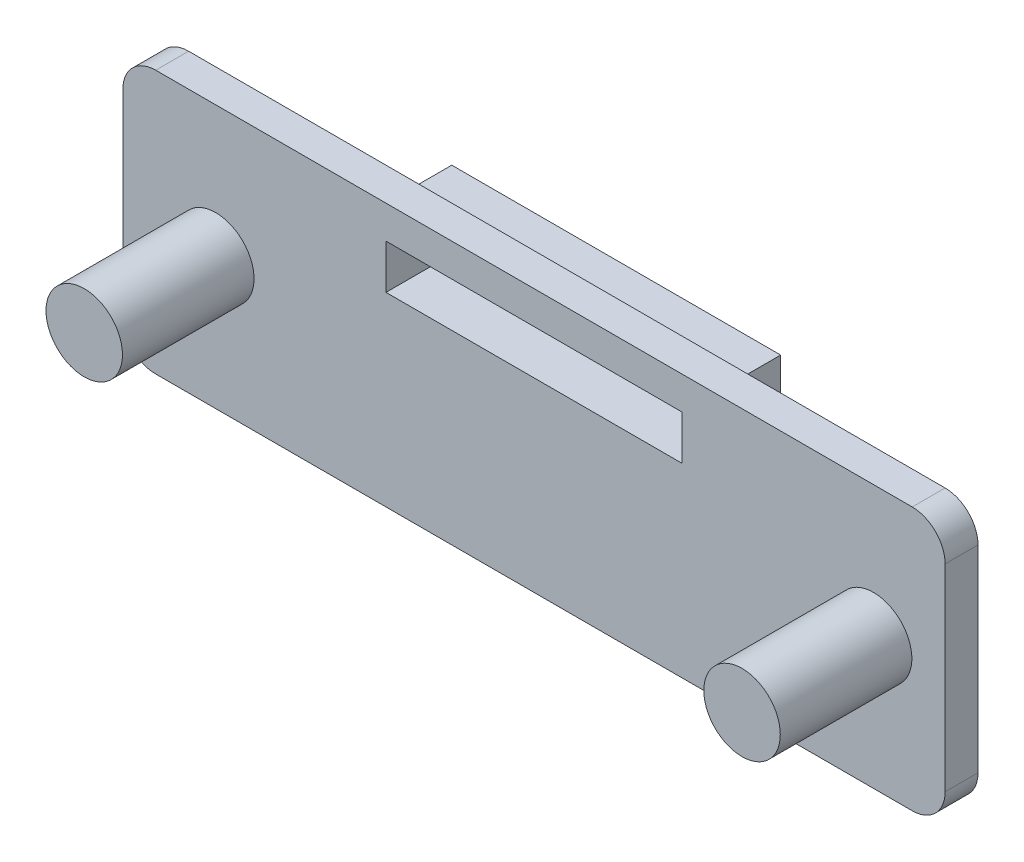
SolidWorks part; units mm, degrees
ref_plane "Front Plane" through (0, 0, 0) normal (0, 0, 1) x (1, 0, 0)
ref_plane "Top Plane" through (0, 0, 0) normal (0, 1, 0) x (1, 0, 0)
ref_plane "Right Plane" through (0, 0, 0) normal (1, 0, 0) x (0, 0, -1)
sketch "Sketch1" plane through (0, 0, 0) normal (0, 0, 1) x (1, 0, 0)
  line L1 (19.6731, 18.1726) -> (-30.3269, 18.1726)
  line L2 (19.6731, 18.1726) -> (19.6731, 2.1726)
  line L3 (19.6731, 2.1726) -> (-30.3269, 2.1726)
  line L4 (-30.3269, 18.1726) -> (-30.3269, 2.1726)
  dimension "D1" = 50
  dimension "D2" = 16
extrude "Boss-Extrude1" add sketch "Sketch1" along normal blind 2
sketch "Sketch2" plane through (0, 0, 2) normal (0, 0, 1) x (1, 0, 0)
  circle A0 centre (-24.6752, 10.1726) radius 2.325
  circle A5 centre (15.3248, 10.1726) radius 2.325
  circle A6 centre (-16.6752, 10.1726) radius 2.325 [skipped]
  circle A7 centre (-8.6752, 10.1726) radius 2.325 [skipped]
  circle A8 centre (-0.6752, 10.1726) radius 2.325 [skipped]
  circle A9 centre (7.3248, 10.1726) radius 2.325 [skipped]
  dimension "D2" = 4.65
  dimension "D1" = 6
extrude "Boss-Extrude2" add sketch "Sketch2" along normal blind 8
fillet "Fillet1" radius 2 4 edges at (19.6731, 18.1726, 1) (19.6731, 2.1726, 1) (-30.3269, 2.1726, 1) (-30.3269, 18.1726, 1)
sketch "Sketch3" plane through (0, 0, 0) normal (0, 0, -1) x (-1, 0, 0)
  line L0 (-4.6731, 10.1726) -> (-19.6731, 10.1726) construction
  line L1 (-4.6731, 17.1726) -> (15.3269, 17.1726)
  line L2 (-4.6731, 17.1726) -> (-4.6731, 3.1726)
  line L3 (-4.6731, 3.1726) -> (15.3269, 3.1726)
  line L4 (15.3269, 17.1726) -> (15.3269, 3.1726)
  line L5 (-19.6731, 4.1726) -> (-19.6731, 16.1726) construction
  line L6 (15.3269, 10.1726) -> (30.3269, 10.1726) construction
  line L7 (30.3269, 16.1726) -> (30.3269, 4.1726) construction
  line L8 (7.139, 17.1726) -> (7.1601, 18.1726) construction
  line L9 (-17.6731, 18.1726) -> (28.3269, 18.1726) construction
  dimension "D1" = 20
  dimension "D2" = 14
  dimension "D3" = 15
  dimension "D4" = 15
  dimension "D5" = 1
extrude "Boss-Extrude3" add sketch "Sketch3" along normal blind 3
sketch "Sketch6" plane through (0, 0, -3) normal (0, 0, -1) x (-1, 0, 0)
  line L0 (7.043, 16.1726) -> (7.043, 17.1726) construction
  line L1 (-3.6731, 16.1726) -> (14.3269, 16.1726)
  line L2 (-3.6731, 16.1726) -> (-3.6731, 13.4726)
  line L3 (-3.6731, 13.4726) -> (14.3269, 13.4726)
  line L4 (14.3269, 16.1726) -> (14.3269, 13.4726)
  line L5 (15.3269, 17.1726) -> (-4.6731, 17.1726) construction
  line L6 (14.3269, 15.1743) -> (15.3269, 15.1743) construction
  line L7 (15.3269, 3.1726) -> (15.3269, 17.1726) construction
  dimension "D1" = 1
  dimension "D2" = 1
  dimension "D3" = 18
  dimension "D4" = 2.7
extrude "Cut-Extrude1" cut sketch "Sketch6" against normal blind 5
